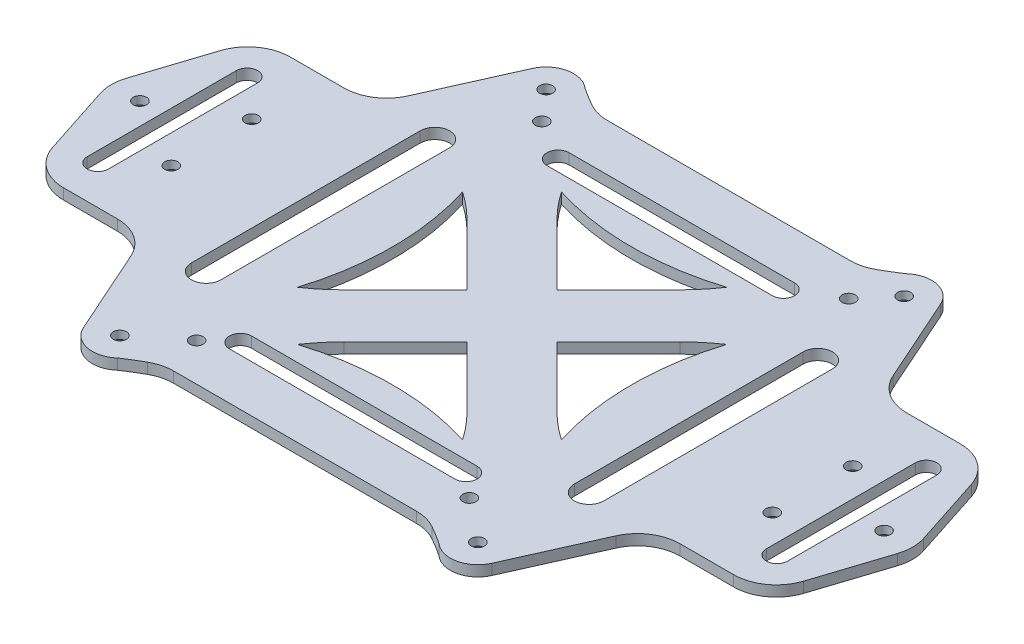
SolidWorks part; units mm, degrees
material "PPS"
ref_plane "前视基准面" through (0, 0, 0) normal (0, 0, 1) x (1, 0, 0)
ref_plane "上视基准面" through (0, 0, 0) normal (0, 1, 0) x (1, 0, 0)
ref_plane "右视基准面" through (0, 0, 0) normal (1, 0, 0) x (0, 0, -1)
sketch "参考" plane through (0, 0, 0) normal (0, 1, 0) x (1, 0, 0)
  line L3 (-133.7177, 0) -> (146.3754, 0) construction
  line L56 (0, 96.0639) -> (0, -115.1457) construction
  line L177 (114.5911, 7.4683) -> (114.5911, -7.4683)
  line L178 (114.5911, 7.4683) -> (43.1936, 17.6463)
  line L179 (114.5911, -7.4683) -> (43.1936, -17.6463)
  line L180 (-114.5911, -7.4683) -> (-43.1936, -17.6463)
  line L181 (-114.5911, 7.4683) -> (-114.5911, -7.4683)
  line L182 (-114.5911, 7.4683) -> (-43.1936, 17.6463)
  arc A18 (-37.7098, 54.831) -> (37.7098, 54.831) centre (0, 111.5317) ccw
  arc A20 (48.2756, 48.4632) -> (43.1936, 17.6463) centre (246.1791, 0) ccw
  arc A21 (48.2756, 48.4632) -> (37.7098, 54.831) centre (42, 50) ccw
  arc A22 (-37.7098, -54.831) -> (37.7098, -54.831) centre (0, -111.5317) cw
  arc A23 (48.2756, -48.4632) -> (43.1936, -17.6463) centre (246.1791, 0) cw
  arc A24 (48.2756, -48.4632) -> (37.7098, -54.831) centre (42, -50) cw
  arc A26 (-48.2756, -48.4632) -> (-37.7098, -54.831) centre (-42, -50) ccw
  arc A27 (-48.2756, -48.4632) -> (-43.1936, -17.6463) centre (-246.1791, 0) ccw
  arc A28 (-48.2756, 48.4632) -> (-37.7098, 54.831) centre (-42, 50) cw
  arc A30 (-48.2756, 48.4632) -> (-43.1936, 17.6463) centre (-246.1791, 0) cw
  dimension "D11" = 50
  dimension "D12" = 42
sketch "草图1" plane through (0, 0, 0) normal (0, 1, 0) x (1, 0, 0)
  line L0 (-160.1541, 0) -> (172.3115, 0) construction
  line L1 (0, 124.2182) -> (0, -143.4382) construction
  line L2 (79.6696, -17.5) -> (79.6696, 17.5) construction
  line L3 (77.1696, -17.5) -> (77.1696, 17.5)
  line L4 (82.1696, -17.5) -> (82.1696, 17.5)
  line L5 (-133.7177, 0) -> (146.3754, 0) construction
  line L6 (47.9, 52.6334) -> (59.525, 26.5883)
  line L7 (59.525, 26.5883) -> (85.8696, 26.5883)
  line L8 (85.8696, 26.5883) -> (94.5058, 0)
  line L9 (59.525, -26.5883) -> (85.8696, -26.5883)
  line L10 (47.9, -52.6334) -> (59.525, -26.5883)
  line L11 (85.8696, -26.5883) -> (94.5058, 0)
  line L12 (-47.9, -52.6334) -> (-59.525, -26.5883)
  line L13 (-59.525, -26.5883) -> (-85.8696, -26.5883)
  line L14 (-85.8696, -26.5883) -> (-94.5058, 0)
  line L15 (-85.8696, 26.5883) -> (-94.5058, 0)
  line L16 (-47.9, 52.6334) -> (-59.525, 26.5883)
  line L17 (-59.525, 26.5883) -> (-85.8696, 26.5883)
  line L18 (-79.6696, -17.5) -> (-79.6696, 17.5) construction
  line L19 (-77.1696, -17.5) -> (-77.1696, 17.5)
  line L20 (-82.1696, -17.5) -> (-82.1696, 17.5)
  line L21 (-24.996, 14.4296) -> (-10.5664, 0)
  line L22 (14.4296, 24.996) -> (0, 10.5664)
  line L23 (-24.996, -14.4296) -> (-10.5664, 0)
  line L24 (-14.4296, 24.996) -> (0, 10.5664)
  line L25 (0, 96.0639) -> (0, -115.1457) construction
  line L26 (24.996, -14.4296) -> (10.5664, 0)
  line L27 (24.996, 14.4296) -> (10.5664, 0)
  line L28 (-14.4296, -24.996) -> (0, -10.5664)
  line L29 (14.4296, -24.996) -> (0, -10.5664)
  line L30 (44.9192, -26.8293) -> (44.9192, 26.8293) construction
  line L31 (41.4687, -26.8293) -> (41.4687, 26.8293)
  line L32 (48.3697, -26.8293) -> (48.3697, 26.8293)
  line L33 (-26.4535, -37.2441) -> (26.4535, -37.2441) construction
  line L34 (-26.4535, -34.637) -> (26.4535, -34.637)
  line L35 (-26.4535, -39.8513) -> (26.4535, -39.8513)
  line L36 (-26.4535, 37.2441) -> (26.4535, 37.2441) construction
  line L37 (-26.4535, 34.637) -> (26.4535, 34.637)
  line L38 (-26.4535, 39.8513) -> (26.4535, 39.8513)
  line L39 (-44.9192, -26.8293) -> (-44.9192, 26.8293) construction
  line L40 (-41.4687, -26.8293) -> (-41.4687, 26.8293)
  line L41 (-48.3697, -26.8293) -> (-48.3697, 26.8293)
  line L42 (-30.9782, 50.8906) -> (30.9782, 50.8906)
  line L43 (-30.9782, -50.8906) -> (30.9782, -50.8906)
  circle A6 centre (42, 50) radius 1.55
  circle A7 centre (42, -50) radius 1.55
  circle A8 centre (-42, -50) radius 1.55
  circle A9 centre (-42, 50) radius 1.55
  circle A10 centre (36, 43) radius 1.55
  circle A11 centre (32, -42) radius 1.55
  circle A12 centre (-32, -42) radius 1.55
  circle A13 centre (-36, 43) radius 1.55
  arc A14 (47.9, 52.6334) -> (37.7098, 54.831) centre (42, 50) ccw
  arc A15 (-37.7098, 54.831) -> (-30.9782, 50.8906) centre (0, 111.5317) ccw
  arc A18 (77.1696, -17.5) -> (82.1696, -17.5) centre (79.6696, -17.5) ccw
  arc A19 (82.1696, 17.5) -> (77.1696, 17.5) centre (79.6696, 17.5) ccw
  circle A20 centre (70.5, 9.4358) radius 1.55
  circle A21 centre (70.5, -9.4358) radius 1.55
  circle A22 centre (-70.5, -9.4358) radius 1.55
  circle A23 centre (-70.5, 9.4358) radius 1.55
  circle A24 centre (87.3, 0) radius 1.55
  arc A25 (48.2756, 48.4632) -> (37.7098, 54.831) centre (42, 50) ccw construction
  arc A26 (47.9, -52.6334) -> (37.7098, -54.831) centre (42, -50) cw
  arc A27 (-37.7098, -54.831) -> (-30.9782, -50.8906) centre (0, -111.5317) cw
  arc A28 (-47.9, 52.6334) -> (-37.7098, 54.831) centre (-42, 50) cw
  arc A29 (-77.1696, -17.5) -> (-82.1696, -17.5) centre (-79.6696, -17.5) cw
  arc A30 (-82.1696, 17.5) -> (-77.1696, 17.5) centre (-79.6696, 17.5) cw
  circle A31 centre (-87.3, 0) radius 1.55
  arc A32 (-47.9, -52.6334) -> (-37.7098, -54.831) centre (-42, -50) ccw
  arc A33 (-24.996, 14.4296) -> (-30.9782, 19.3706) centre (-53.9062, -14.4807) ccw
  arc A34 (-24.996, -14.4296) -> (-30.9782, -19.3706) centre (-53.9062, 14.4807) cw
  arc A35 (-30.9782, -19.3706) -> (-30.9782, 19.3706) centre (-93.0146, 0) ccw
  arc A36 (-14.4296, 24.996) -> (-19.3706, 30.9782) centre (14.4807, 53.9062) cw
  arc A37 (-19.3706, 30.9782) -> (19.3706, 30.9782) centre (0, 93.0146) ccw
  arc A38 (14.4296, 24.996) -> (19.3706, 30.9782) centre (-14.4807, 53.9062) ccw
  arc A39 (24.996, 14.4296) -> (30.9782, 19.3706) centre (53.9062, -14.4807) cw
  arc A40 (30.9782, 19.3706) -> (30.9782, -19.3706) centre (93.0146, 0) ccw
  arc A41 (24.996, -14.4296) -> (30.9782, -19.3706) centre (53.9062, 14.4807) ccw
  arc A42 (14.4296, -24.996) -> (19.3706, -30.9782) centre (-14.4807, -53.9062) cw
  arc A43 (19.3706, -30.9782) -> (-19.3706, -30.9782) centre (0, -93.0146) ccw
  arc A44 (-14.4296, -24.996) -> (-19.3706, -30.9782) centre (14.4807, -53.9062) ccw
  arc A45 (41.4687, -26.8293) -> (48.3697, -26.8293) centre (44.9192, -26.8293) ccw
  arc A46 (48.3697, 26.8293) -> (41.4687, 26.8293) centre (44.9192, 26.8293) ccw
  arc A47 (-26.4535, -34.637) -> (-26.4535, -39.8513) centre (-26.4535, -37.2441) ccw
  arc A48 (26.4535, -39.8513) -> (26.4535, -34.637) centre (26.4535, -37.2441) ccw
  arc A49 (-26.4535, 34.637) -> (-26.4535, 39.8513) centre (-26.4535, 37.2441) cw
  arc A50 (26.4535, 39.8513) -> (26.4535, 34.637) centre (26.4535, 37.2441) cw
  arc A51 (-41.4687, -26.8293) -> (-48.3697, -26.8293) centre (-44.9192, -26.8293) cw
  arc A52 (-48.3697, 26.8293) -> (-41.4687, 26.8293) centre (-44.9192, 26.8293) cw
  arc A53 (30.9782, 50.8906) -> (37.7098, 54.831) centre (0, 111.5317) ccw
  arc A54 (30.9782, -50.8906) -> (37.7098, -54.831) centre (0, -111.5317) cw
  point P30 (79.6696, 0)
  point P63 (44.9192, 0)
  point P78 (-79.6696, 0)
  point P98 (0, 0)
  point P116 (0, -37.2441)
  point P129 (0, 37.2441)
  point P136 (-44.9192, 0)
  dimension "D1" = 50
  dimension "D3" = 3.1
  dimension "D8" = 2.5
  dimension "D10" = 3.1
  dimension "D12" = 3.1
  dimension "D2" = 42
  dimension "D4" = 36
  dimension "D5" = 32
  dimension "D6" = 42
  dimension "D7" = 43
  dimension "D9" = 35
  dimension "D11" = 70.5
  dimension "D13" = 87.3
  dimension "D14" = 4
extrude "凸台-拉伸1" add sketch "草图1" along normal blind 2.5
fillet "圆角1" radius 10 14 edges at (59.525, 1.25, -26.5883) (85.8696, 1.25, -26.5883) (85.8696, 1.25, 26.5883) (94.5058, 1.25, 0) (59.525, 1.25, 26.5883) (-59.525, 1.25, 26.5883) (-59.525, 1.25, -26.5883) (-85.8696, 1.25, -26.5883) (-85.8696, 1.25, 26.5883) (-94.5058, 1.25, 0) (30.9782, 1.25, -50.8906) (-30.9782, 1.25, -50.8906) (30.9782, 1.25, 50.8906) (-30.9782, 1.25, 50.8906)
chamfer "倒角2" distance 0.615 angle 30 10 edges at (-70.5, 0, 10.9858) (-70.5, 0, -10.9858) (70.5, 0, 7.8858) (70.5, 0, -7.8858) (-87.3, 0, -1.55) (87.3, 0, 1.55) (-42, 0, 51.55) (42, 0, 48.45) (-42, 0, -51.55) (42, 0, -48.45)
